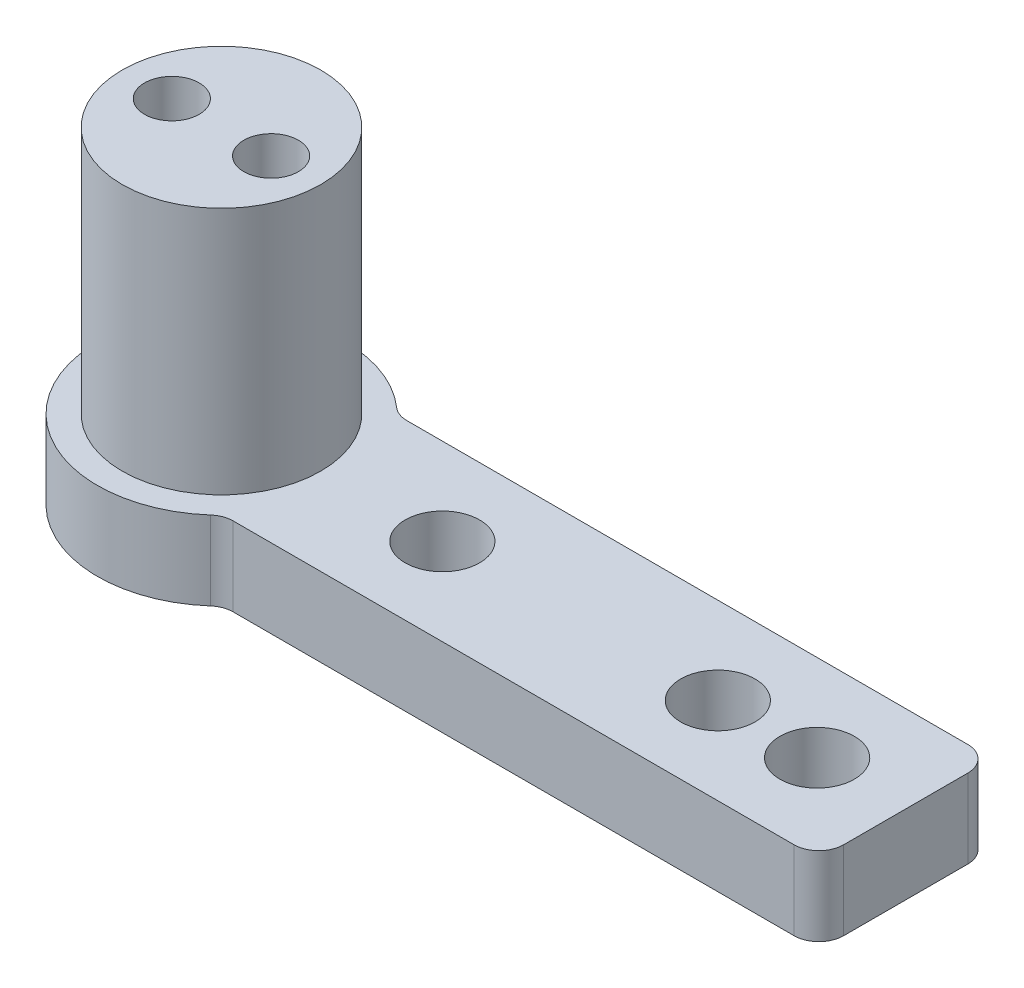
SolidWorks part; units mm, degrees
ref_plane "Front Plane" through (0, 0, 0) normal (0, 0, 1) x (1, 0, 0)
ref_plane "Top Plane" through (0, 0, 0) normal (0, 1, 0) x (1, 0, 0)
ref_plane "Right Plane" through (0, 0, 0) normal (1, 0, 0) x (0, 0, -1)
sketch "Sketch1" plane through (0, 0, 0) normal (0, 1, 0) x (1, 0, 0)
  line L1 (3.5707, 3.5) -> (27.5707, 3.5)
  line L3 (3.5707, -3.5) -> (27.5707, -3.5)
  line L4 (27.5707, 3.5) -> (27.5707, -3.5)
  arc A0 (3.5707, 3.5) -> (3.5707, -3.5) centre (0, 0) ccw
  circle A1 centre (8.9, 0) radius 1.5
  circle A2 centre (20, 0) radius 1.5
  circle A3 centre (24, 0) radius 1.5
  point P7 (27.5707, 0)
  point P13 (0, 0)
  point P14 (0, 0)
  dimension "D1" = 10
  dimension "D3" = 3
  dimension "D2" = 24
  dimension "D4" = 8.9
  dimension "D5" = 11.1
  dimension "D6" = 4
  dimension "D7" = 7
extrude "Boss-Extrude1" add sketch "Sketch1" along normal blind 3.175
sketch "Sketch2" plane through (0, 3.175, 0) normal (0, 1, 0) x (1, 0, 0)
  circle A0 centre (0, 0) radius 4
  dimension "D1" = 8
extrude "Boss-Extrude2" add sketch "Sketch2" along normal blind 10
fillet "Fillet1" radius 1 4 edges at (3.5707, 1.5875, -3.5) (3.5707, 1.5875, 3.5) (27.5707, 1.5875, -3.5) (27.5707, 1.5875, 3.5)
sketch "Sketch3" plane through (0, 13.175, 0) normal (0, 1, 0) x (1, 0, 0)
  circle A0 centre (2, 0) radius 1.1
  circle A1 centre (-2, 0) radius 1.1
  point P4 (0, 0)
  dimension "D3" = 2.2
  dimension "D1" = 2
  dimension "D2" = 2
extrude "Cut-Extrude1" cut sketch "Sketch3" against normal blind 5
